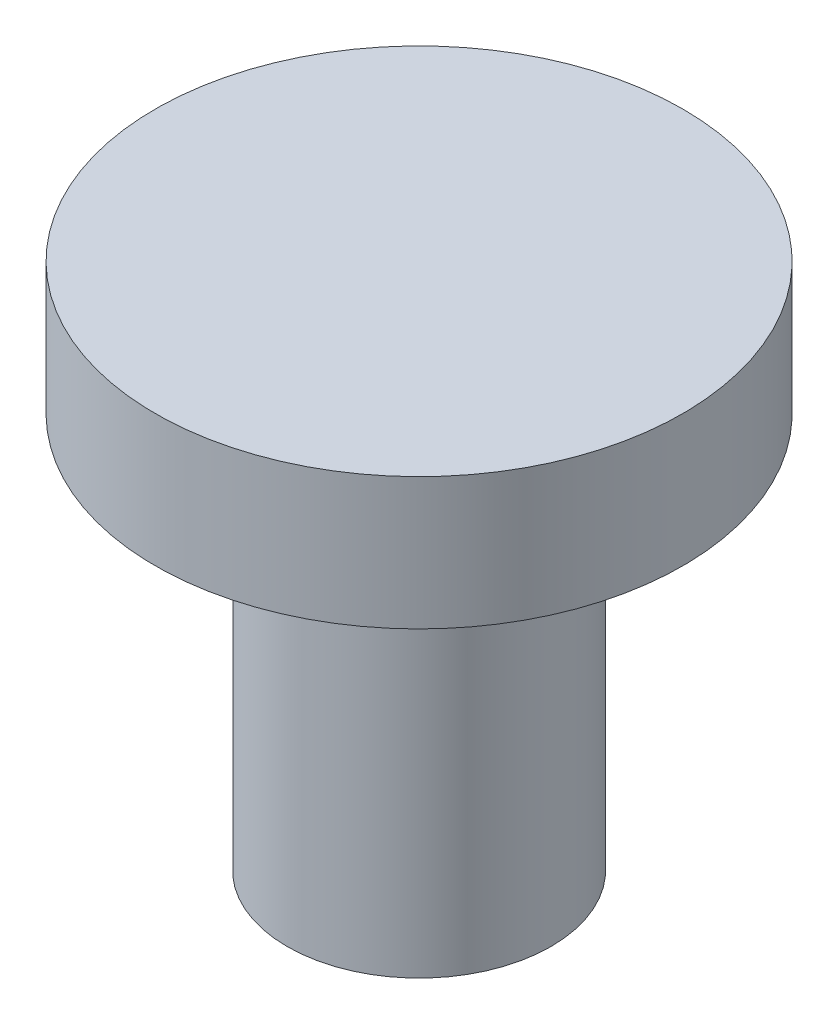
SolidWorks part; units mm, degrees
ref_plane "Front Plane" through (0, 0, 0) normal (0, 0, 1) x (1, 0, 0)
ref_plane "Top Plane" through (0, 0, 0) normal (0, 1, 0) x (1, 0, 0)
ref_plane "Right Plane" through (0, 0, 0) normal (1, 0, 0) x (0, 0, -1)
sketch "Sketch1" plane through (0, 0, 0) normal (0, 0, 1) x (1, 0, 0)
  line L0 (2, 4) -> (0, 4)
  line L1 (0, 4) -> (0, 0)
  line L2 (0, 0) -> (1, 0)
  line L3 (1, 0) -> (1, 3)
  line L4 (1, 3) -> (2, 3)
  line L5 (2, 3) -> (2, 4)
  line L6 (0, 4) -> (0, 0) construction
revolve "Revolve1" add sketch "Sketch1" angle 360 about L6
